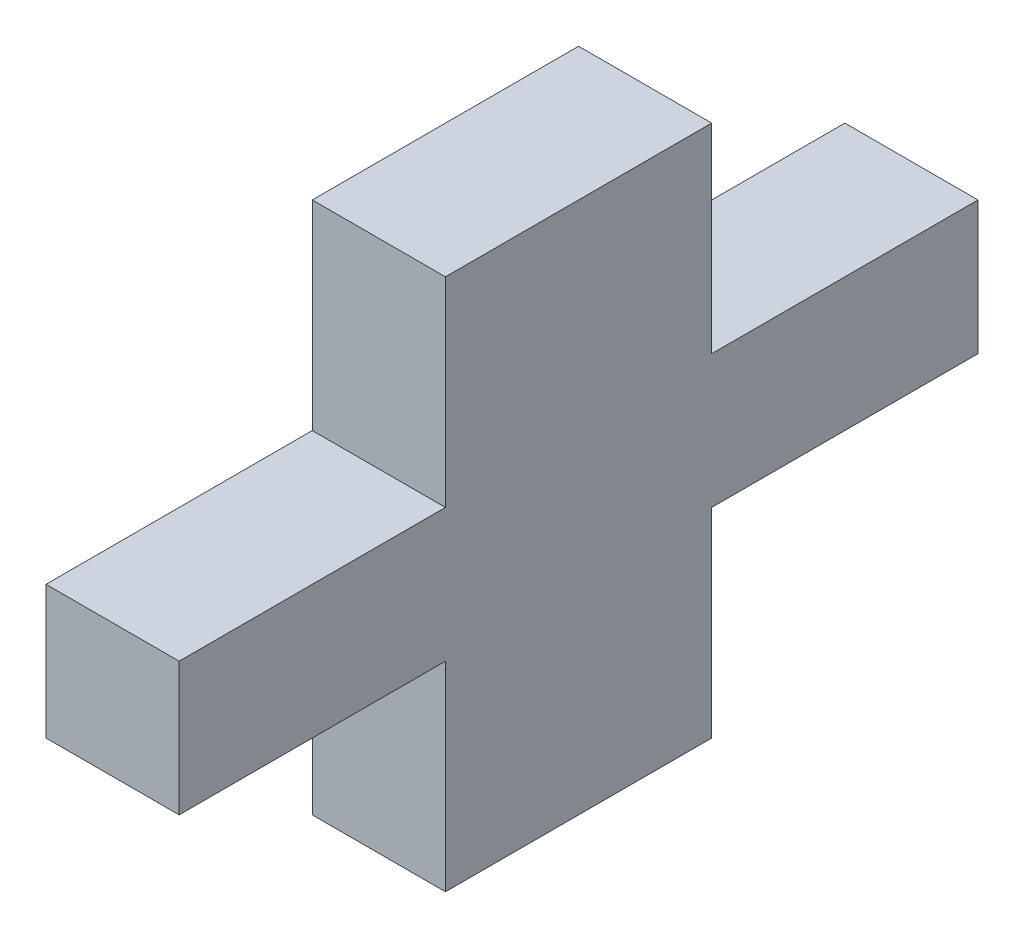
SolidWorks part; units mm, degrees
ref_plane "Front Plane" through (0, 0, 0) normal (0, 0, 1) x (1, 0, 0)
ref_plane "Top Plane" through (0, 0, 0) normal (0, 1, 0) x (1, 0, 0)
ref_plane "Right Plane" through (0, 0, 0) normal (1, 0, 0) x (0, 0, -1)
sketch "Sketch3" plane through (0, 0, 0) normal (1, 0, 0) x (0, 0, -1)
  line L0 (-45.1351, 0) -> (42.8829, 0) construction
  line L1 (0, 27.8829) -> (0, -31.5766) construction
  line L2 (10, 20) -> (-10, 20)
  line L3 (-10, 20) -> (-10, 5)
  line L4 (-10, 5) -> (-30, 5)
  line L5 (-30, 5) -> (-30, -5)
  line L6 (30, 5) -> (30, -5)
  line L7 (10, 5) -> (30, 5)
  line L8 (10, 20) -> (10, 5)
  line L9 (0, -27.8829) -> (0, 31.5766) construction
  line L10 (10, -20) -> (10, -5)
  line L11 (10, -5) -> (30, -5)
  line L12 (-10, -5) -> (-30, -5)
  line L13 (-10, -20) -> (-10, -5)
  line L14 (10, -20) -> (-10, -20)
  point P14 (0, 20)
  point P19 (30, 0)
  point P20 (-30, 0)
  point P22 (0, -20)
  dimension "D1" = 10
  dimension "D2" = 5
  dimension "D3" = 15
  dimension "D4" = 20
extrude "Boss-Extrude2" add sketch "Sketch3" along normal blind 10
